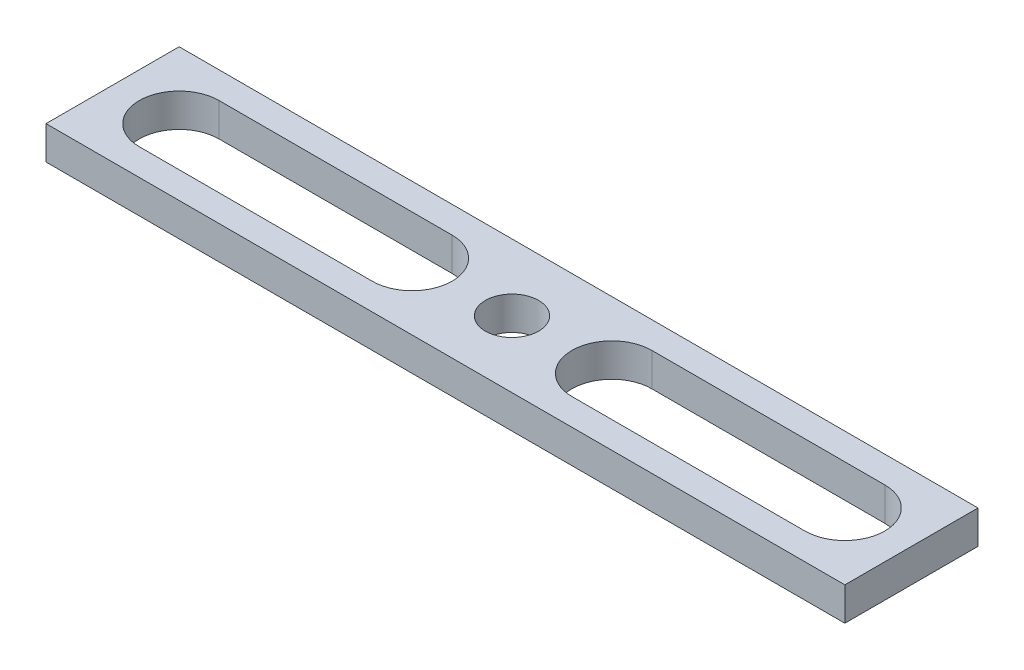
SolidWorks part; units mm, degrees
ref_plane "Front Plane" through (0, 0, 0) normal (0, 0, 1) x (1, 0, 0)
ref_plane "Top Plane" through (0, 0, 0) normal (0, 1, 0) x (1, 0, 0)
ref_plane "Right Plane" through (0, 0, 0) normal (1, 0, 0) x (0, 0, -1)
sketch "Sketch1" plane through (0, 0, 0) normal (0, 1, 0) x (1, 0, 0)
  line L1 (-38.1, 6.35) -> (38.1, 6.35)
  line L2 (-38.1, 6.35) -> (-38.1, -6.35)
  line L3 (-38.1, -6.35) -> (38.1, -6.35)
  line L4 (38.1, 6.35) -> (38.1, -6.35)
  dimension "D1" = 76.2
  dimension "D2" = 12.7
  dimension "D3" = 38.1
  dimension "D4" = 6.35
extrude "Boss-Extrude1" add sketch "Sketch1" along normal blind 3.175
sketch "Sketch2" plane through (0, 3.175, 0) normal (0, 1, 0) x (1, 0, 0)
  circle A0 centre (0, 0) radius 2.54
  dimension "D1" = 5.08
extrude "Cut-Extrude1" cut sketch "Sketch2" against normal through all
sketch "Sketch4" plane through (0, 3.175, 0) normal (0, 1, 0) x (1, 0, 0)
  line L0 (-31.75, 0) -> (-9.525, 0) construction
  line L1 (-31.75, 3.81) -> (-9.525, 3.81)
  line L2 (-31.75, -3.81) -> (-9.525, -3.81)
  line L3 (9.525, 0) -> (31.75, 0) construction
  line L4 (9.525, 3.81) -> (31.75, 3.81)
  line L5 (9.525, -3.81) -> (31.75, -3.81)
  line L6 (-38.1, 6.35) -> (-38.1, -6.35) construction
  line L7 (38.1, -6.35) -> (38.1, 6.35) construction
  arc A0 (-31.75, 3.81) -> (-31.75, -3.81) centre (-31.75, 0) ccw
  arc A1 (-9.525, -3.81) -> (-9.525, 3.81) centre (-9.525, 0) ccw
  arc A2 (9.525, 3.81) -> (9.525, -3.81) centre (9.525, 0) ccw
  arc A3 (31.75, -3.81) -> (31.75, 3.81) centre (31.75, 0) ccw
  point P3 (-20.6375, 0)
  point P8 (20.6375, 0)
  point P15 (-38.1, 0)
  point P18 (38.1, 0)
  dimension "D1" = 7.62
  dimension "D2" = 6.35
  dimension "D3" = 6.35
  dimension "D4" = 9.525
extrude "Cut-Extrude2" cut sketch "Sketch4" against normal through all
